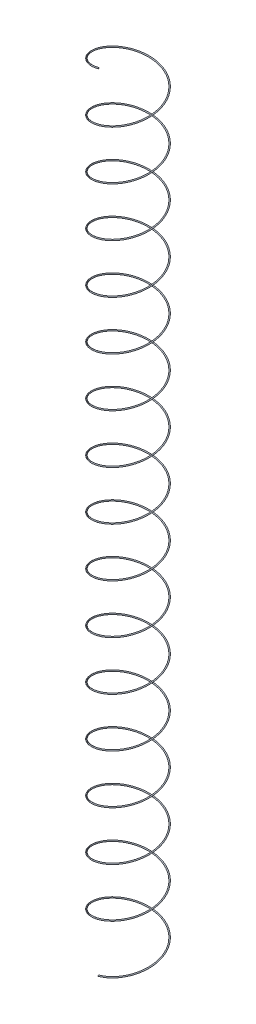
SolidWorks part; units mm, degrees
ref_plane "Front Plane" through (0, 0, 0) normal (0, 0, 1) x (1, 0, 0)
ref_plane "Top Plane" through (0, 0, 0) normal (0, 1, 0) x (1, 0, 0)
ref_plane "Right Plane" through (0, 0, 0) normal (1, 0, 0) x (0, 0, -1)
sketch "Center Axis" plane through (0, 0, 0) normal (1, 0, 0) x (0, 0, -1)
  line L0 (0, 0) -> (0, 49.506) construction
sketch "Diameter Stowed" plane through (0, 0, 0) normal (0, 1, 0) x (1, 0, 0)
  circle A0 centre (0, 0) radius 22.495
  dimension "D1" = 44.99
sketch "Diameter Deployed" plane through (0, 0, 0) normal (0, 1, 0) x (1, 0, 0)
  circle A0 centre (0, 0) radius 22.75
  dimension "D1" = 45.5
sketch "Wire Gauge XZ" plane through (0, 0, 0) normal (0, 1, 0) x (1, 0, 0)
  circle A0 centre (0, 0) radius 0.405
  dimension "D1" = 0.81
sketch "Wire Gauge YZ" plane through (0, 0, 0) normal (1, 0, 0) x (0, 0, -1)
  line L0 (0.405, 0) -> (-0.405, 0) construction
  line L1 (0, 0) -> (-0.405, 0) construction
  circle A0 centre (0, 0) radius 0.405
curve "Deployed Helix" pitch 38 height 608 turns 16
sketch "Sketch7" plane through (0, 0, 0) normal (1, 0, 0) x (0, 0, -1)
  circle A0 centre (-22.75, 0) radius 0.405
  circle A1 centre (0, 0) radius 0.405 construction
  spline S0 degree 3 poles (-22.75, 0) (-22.75, 0.5889) (-22.0939, 1.7735) (-19.2253, 3.5449) (-14.717, 5.3178) (-8.9535, 7.0904) (-2.4263, 8.863) (4.3078, 10.6356) (10.6745, 12.4082) (16.1308, 14.1808) (20.2112, 15.9534) (22.5679, 17.7259) (22.9997, 19.4985) (21.4699, 21.2711) (18.1089, 23.0437) (13.2033, 24.8163) (7.1717, 26.5889) (0.5284, 28.3615) (-6.16, 30.1341) (-12.323, 31.9067) (-17.4349, 33.6793) (-21.0599, 35.4519) (-22.8886, 37.2245) (-22.7651, 38.9971) (-20.7, 40.7697) (-16.8694, 42.5423) (-11.6, 44.3149) (-5.3412, 46.0875) (1.3731, 47.8601) (7.9704, 49.6327) (13.8878, 51.4052) (18.6207, 53.1778) (21.7655, 54.9504) (23.0539, 56.723) (22.376, 58.4956) (19.7896, 60.2682) (15.5154, 62.0408) (9.9179, 63.8134) (3.4744, 65.586) (-3.2653, 67.3586) (-9.7266, 69.1312) (-15.3583, 70.9038) (-19.68, 72.6764) (-22.3233, 74.449) (-23.0626, 76.2216) (-21.8348, 77.9942) (-18.7448, 79.7668) (-14.056, 81.5394) (-8.1684, 83.312) (-1.5841, 85.0845) (5.1354, 86.8571) (11.4168, 88.6297) (16.7245, 90.4023) (20.6057, 92.1749) (22.7295, 93.9475) (22.9147, 95.7201) (21.1454, 97.4927) (17.5727, 99.2653) (12.5012, 101.0379) (6.3634, 102.8105) (-0.3171, 104.5831) (-6.9705, 106.3557) (-13.0294, 108.1283) (-17.9771, 109.9009) (-21.3914, 111.6735) (-22.9813, 113.4461) (-22.6111, 115.2187) (-20.3124, 116.9913) (-16.2812, 118.7638) (-10.8614, 120.5364) (-4.5153, 122.309) (2.216, 124.0816) (8.7583, 125.8542) (14.5536, 127.6268) (19.1076, 129.3994) (22.0319, 131.172) (23.0771, 132.9446) (22.154, 134.7172) (19.3414, 136.4898) (14.8792, 138.2624) (9.1479, 140.035) (2.6364, 141.8076) (-4.0999, 143.5802) (-10.4866, 145.3528) (-15.9789, 147.1254) (-20.1083, 148.898) (-22.5227, 150.6706) (-23.0161, 152.4431) (-21.5465, 154.2157) (-18.2391, 155.9883) (-13.3761, 157.7609) (-7.3723, 159.5335) (-0.7397, 161.3061) (5.956, 163.0787) (12.1437, 164.8513) (17.2957, 166.6239) (20.9725, 168.3965) (22.8606, 170.1691) (22.7989, 171.9417) (20.7926, 173.7143) (17.0129, 175.4869) (11.7822, 177.2595) (5.5466, 179.0321) (-1.1621, 180.8047) (-7.7717, 182.5773) (-13.7184, 184.3499) (-18.4951, 186.1224) (-21.6943, 187.895) (-23.0432, 189.6676) (-22.4268, 191.4402) (-19.8975, 193.2128) (-15.6712, 194.9854) (-10.1083, 196.758) (-3.6833, 198.5306) (3.0559, 200.3032) (9.5345, 202.0758) (15.1999, 203.8484) (19.5688, 205.621) (22.2687, 207.3936) (23.0693, 209.1662) (21.9024, 210.9388) (18.8673, 212.7114) (14.2231, 214.484) (8.3657, 216.2566) (1.7949, 218.0292) (-4.9291, 219.8017) (-11.2326, 221.5743) (-16.5781, 223.3469) (-20.5097, 225.1195) (-22.6919, 226.8921) (-22.9388, 228.6647) (-21.2292, 230.4373) (-17.709, 232.2099) (-12.6783, 233.9825) (-6.5663, 235.7551) (0.1057, 237.5277) (6.7687, 239.3003) (12.8544, 241.0729) (17.8438, 242.8455) (21.3112, 244.6181) (22.961, 246.3907) (22.6525, 248.1633) (20.4119, 249.9359) (16.4304, 251.7085) (11.0475, 253.481) (4.7224, 255.2536) (-2.0055, 257.0262) (-8.5624, 258.7988) (-14.3889, 260.5714) (-18.9882, 262.344) (-21.968, 264.1166) (-23.0742, 265.8892) (-22.2123, 267.6618) (-19.4559, 269.4344) (-15.0402, 271.207) (-9.3416, 272.9796) (-2.8463, 274.7522) (3.8918, 276.5248) (10.2979, 278.2974) (15.8257, 280.07) (20.0038, 281.8426) (22.4757, 283.6152) (23.0306, 285.3878) (21.6213, 287.1603) (18.3679, 288.9329) (13.5478, 290.7055) (7.5723, 292.4781) (0.9509, 294.2507) (-5.7516, 296.0233) (-11.9635, 297.7959) (-17.1551, 299.5685) (-20.8834, 301.3411) (-22.8307, 303.1137) (-22.8307, 304.8863) (-20.8834, 306.6589) (-17.1551, 308.4315) (-11.9635, 310.2041) (-5.7516, 311.9767) (0.9509, 313.7493) (7.5723, 315.5219) (13.5478, 317.2945) (18.3679, 319.0671) (21.6213, 320.8397) (23.0306, 322.6122) (22.4757, 324.3848) (20.0038, 326.1574) (15.8257, 327.93) (10.2979, 329.7026) (3.8918, 331.4752) (-2.8463, 333.2478) (-9.3416, 335.0204) (-15.0402, 336.793) (-19.4559, 338.5656) (-22.2123, 340.3382) (-23.0742, 342.1108) (-21.968, 343.8834) (-18.9882, 345.656) (-14.3889, 347.4286) (-8.5624, 349.2012) (-2.0055, 350.9738) (4.7224, 352.7464) (11.0475, 354.519) (16.4304, 356.2915) (20.4119, 358.0641) (22.6525, 359.8367) (22.961, 361.6093) (21.3112, 363.3819) (17.8438, 365.1545) (12.8544, 366.9271) (6.7687, 368.6997) (0.1057, 370.4723) (-6.5663, 372.2449) (-12.6783, 374.0175) (-17.709, 375.7901) (-21.2292, 377.5627) (-22.9388, 379.3353) (-22.6919, 381.1079) (-20.5097, 382.8805) (-16.5781, 384.6531) (-11.2326, 386.4257) (-4.9291, 388.1983) (1.7949, 389.9708) (8.3657, 391.7434) (14.2231, 393.516) (18.8673, 395.2886) (21.9024, 397.0612) (23.0693, 398.8338) (22.2687, 400.6064) (19.5688, 402.379) (15.1999, 404.1516) (9.5345, 405.9242) (3.0559, 407.6968) (-3.6833, 409.4694) (-10.1083, 411.242) (-15.6712, 413.0146) (-19.8975, 414.7872) (-22.4268, 416.5598) (-23.0432, 418.3324) (-21.6943, 420.105) (-18.4951, 421.8776) (-13.7184, 423.6501) (-7.7717, 425.4227) (-1.1621, 427.1953) (5.5466, 428.9679) (11.7822, 430.7405) (17.0129, 432.5131) (20.7926, 434.2857) (22.7989, 436.0583) (22.8606, 437.8309) (20.9725, 439.6035) (17.2957, 441.3761) (12.1437, 443.1487) (5.956, 444.9213) (-0.7397, 446.6939) (-7.3723, 448.4665) (-13.3761, 450.2391) (-18.2391, 452.0117) (-21.5465, 453.7843) (-23.0161, 455.5569) (-22.5227, 457.3294) (-20.1083, 459.102) (-15.9789, 460.8746) (-10.4866, 462.6472) (-4.0999, 464.4198) (2.6364, 466.1924) (9.1479, 467.965) (14.8792, 469.7376) (19.3414, 471.5102) (22.154, 473.2828) (23.0771, 475.0554) (22.0319, 476.828) (19.1076, 478.6006) (14.5536, 480.3732) (8.7583, 482.1458) (2.216, 483.9184) (-4.5153, 485.691) (-10.8614, 487.4636) (-16.2812, 489.2362) (-20.3124, 491.0087) (-22.6111, 492.7813) (-22.9813, 494.5539) (-21.3914, 496.3265) (-17.9771, 498.0991) (-13.0294, 499.8717) (-6.9705, 501.6443) (-0.3171, 503.4169) (6.3634, 505.1895) (12.5012, 506.9621) (17.5727, 508.7347) (21.1454, 510.5073) (22.9147, 512.2799) (22.7295, 514.0525) (20.6057, 515.8251) (16.7245, 517.5977) (11.4168, 519.3703) (5.1354, 521.1429) (-1.5841, 522.9155) (-8.1684, 524.688) (-14.056, 526.4606) (-18.7448, 528.2332) (-21.8348, 530.0058) (-23.0626, 531.7784) (-22.3233, 533.551) (-19.68, 535.3236) (-15.3583, 537.0962) (-9.7266, 538.8688) (-3.2653, 540.6414) (3.4744, 542.414) (9.9179, 544.1866) (15.5154, 545.9592) (19.7896, 547.7318) (22.376, 549.5044) (23.0539, 551.277) (21.7655, 553.0496) (18.6207, 554.8222) (13.8878, 556.5948) (7.9704, 558.3673) (1.3731, 560.1399) (-5.3412, 561.9125) (-11.6, 563.6851) (-16.8694, 565.4577) (-20.7, 567.2303) (-22.7651, 569.0029) (-22.8886, 570.7755) (-21.0599, 572.5481) (-17.4349, 574.3207) (-12.323, 576.0933) (-6.16, 577.8659) (0.5284, 579.6385) (7.1717, 581.4111) (13.2033, 583.1837) (18.1089, 584.9563) (21.4699, 586.7289) (22.9997, 588.5015) (22.5679, 590.2741) (20.2112, 592.0466) (16.1308, 593.8192) (10.6745, 595.5918) (4.3078, 597.3644) (-2.4263, 599.137) (-8.9535, 600.9096) (-14.717, 602.6822) (-19.2253, 604.4551) (-22.0939, 606.2265) (-22.75, 607.4111) (-22.75, 608) knots 0 0 0 0 0.002915 0.005831 0.008746 0.011662 0.014577 0.017493 0.020408 0.023324 0.026239 0.029155 0.03207 0.034985 0.037901 0.040816 0.043732 0.046647 0.049563 0.052478 0.055394 0.058309 0.061224 0.06414 0.067055 0.069971 0.072886 0.075802 0.078717 0.081633 0.084548 0.087464 0.090379 0.093294 0.09621 0.099125 0.102041 0.104956 0.107872 0.110787 0.113703 0.116618 0.119534 0.122449 0.125364 0.12828 0.131195 0.134111 0.137026 0.139942 0.142857 0.145773 0.148688 0.151603 0.154519 0.157434 0.16035 0.163265 0.166181 0.169096 0.172012 0.174927 0.177843 0.180758 0.183673 0.186589 0.189504 0.19242 0.195335 0.198251 0.201166 0.204082 0.206997 0.209913 0.212828 0.215743 0.218659 0.221574 0.22449 0.227405 0.230321 0.233236 0.236152 0.239067 0.241983 0.244898 0.247813 0.250729 0.253644 0.25656 0.259475 0.262391 0.265306 0.268222 0.271137 0.274052 0.276968 0.279883 0.282799 0.285714 0.28863 0.291545 0.294461 0.297376 0.300292 0.303207 0.306122 0.309038 0.311953 0.314869 0.317784 0.3207 0.323615 0.326531 0.329446 0.332362 0.335277 0.338192 0.341108 0.344023 0.346939 0.349854 0.35277 0.355685 0.358601 0.361516 0.364431 0.367347 0.370262 0.373178 0.376093 0.379009 0.381924 0.38484 0.387755 0.390671 0.393586 0.396501 0.399417 0.402332 0.405248 0.408163 0.411079 0.413994 0.41691 0.419825 0.422741 0.425656 0.428571 0.431487 0.434402 0.437318 0.440233 0.443149 0.446064 0.44898 0.451895 0.45481 0.457726 0.460641 0.463557 0.466472 0.469388 0.472303 0.475219 0.478134 0.48105 0.483965 0.48688 0.489796 0.492711 0.495627 0.498542 0.501458 0.504373 0.507289 0.510204 0.51312 0.516035 0.51895 0.521866 0.524781 0.527697 0.530612 0.533528 0.536443 0.539359 0.542274 0.54519 0.548105 0.55102 0.553936 0.556851 0.559767 0.562682 0.565598 0.568513 0.571429 0.574344 0.577259 0.580175 0.58309 0.586006 0.588921 0.591837 0.594752 0.597668 0.600583 0.603499 0.606414 0.609329 0.612245 0.61516 0.618076 0.620991 0.623907 0.626822 0.629738 0.632653 0.635569 0.638484 0.641399 0.644315 0.64723 0.650146 0.653061 0.655977 0.658892 0.661808 0.664723 0.667638 0.670554 0.673469 0.676385 0.6793 0.682216 0.685131 0.688047 0.690962 0.693878 0.696793 0.699708 0.702624 0.705539 0.708455 0.71137 0.714286 0.717201 0.720117 0.723032 0.725948 0.728863 0.731778 0.734694 0.737609 0.740525 0.74344 0.746356 0.749271 0.752187 0.755102 0.758017 0.760933 0.763848 0.766764 0.769679 0.772595 0.77551 0.778426 0.781341 0.784257 0.787172 0.790087 0.793003 0.795918 0.798834 0.801749 0.804665 0.80758 0.810496 0.813411 0.816327 0.819242 0.822157 0.825073 0.827988 0.830904 0.833819 0.836735 0.83965 0.842566 0.845481 0.848397 0.851312 0.854227 0.857143 0.860058 0.862974 0.865889 0.868805 0.87172 0.874636 0.877551 0.880466 0.883382 0.886297 0.889213 0.892128 0.895044 0.897959 0.900875 0.90379 0.906706 0.909621 0.912536 0.915452 0.918367 0.921283 0.924198 0.927114 0.930029 0.932945 0.93586 0.938776 0.941691 0.944606 0.947522 0.950437 0.953353 0.956268 0.959184 0.962099 0.965015 0.96793 0.970845 0.973761 0.976676 0.979592 0.982507 0.985423 0.988338 0.991254 0.994169 0.997085 1 1 1 1 construction
  point P2 (0, 0)
  point P4 (0, 0)
sweep "Deployed" add profiles "Sketch7" path "Deployed Helix"
